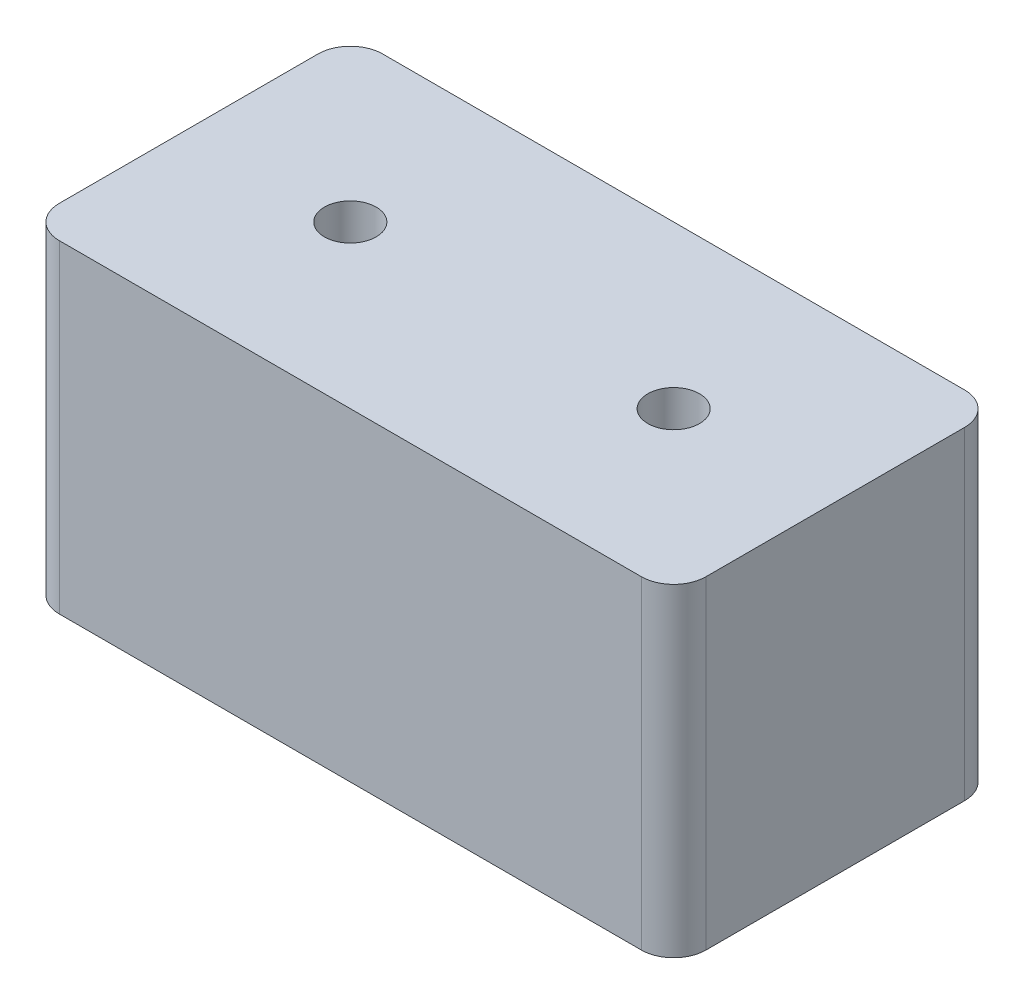
SolidWorks part; units mm, degrees
ref_plane "Front Plane" through (0, 0, 0) normal (0, 0, 1) x (1, 0, 0)
ref_plane "Top Plane" through (0, 0, 0) normal (0, 1, 0) x (1, 0, 0)
ref_plane "Right Plane" through (0, 0, 0) normal (1, 0, 0) x (0, 0, -1)
sketch "Sketch1" plane through (0, 0, 0) normal (0, 1, 0) x (1, 0, 0)
  line L0 (0, 10) -> (40, 10) construction
  line L1 (0, 0) -> (40, 0)
  line L2 (0, 0) -> (0, 20)
  line L3 (0, 20) -> (40, 20)
  line L4 (40, 0) -> (40, 20)
  circle A0 centre (10, 10) radius 1.6
  circle A1 centre (30, 10) radius 1.6
  dimension "D3" = 3.2
  dimension "D4" = 3.2
  dimension "D5" = 10
  dimension "D6" = 10
  dimension "D1" = 40
  dimension "D2" = 20
extrude "Boss-Extrude1" add sketch "Sketch1" along normal blind 20
fillet "Fillet1" radius 2 4 edges at (40, 10, -20) (40, 10, 0) (0, 10, 0) (0, 10, -20)
